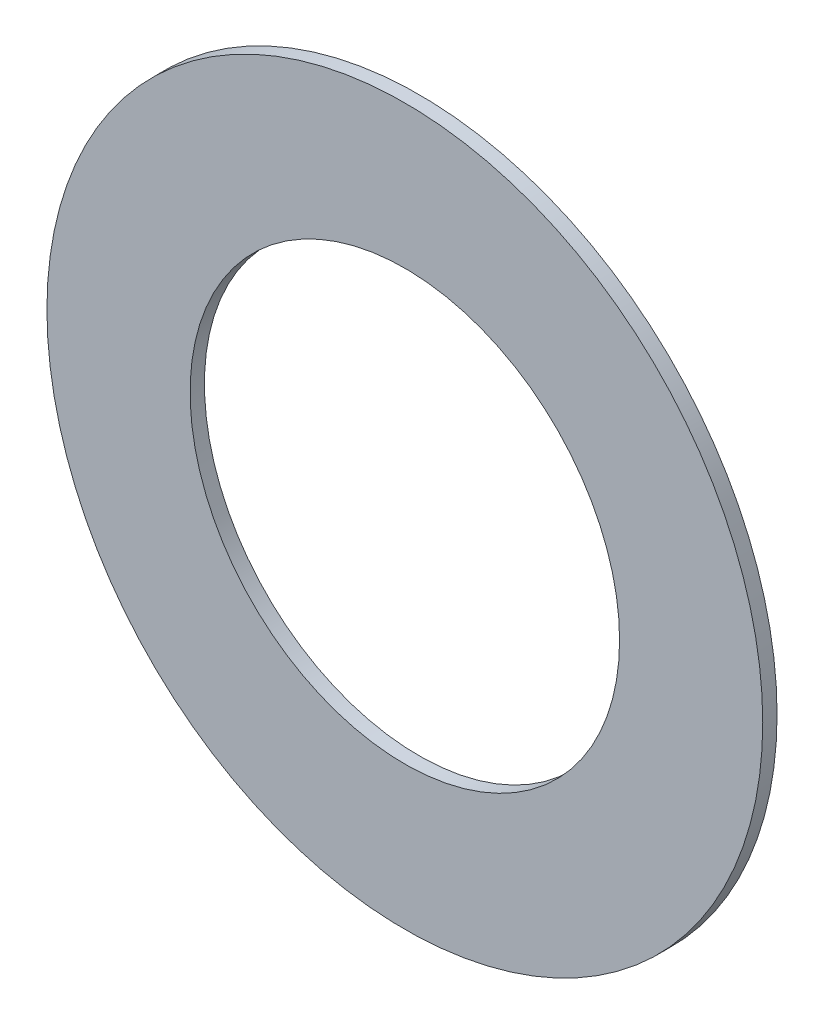
SolidWorks part; units mm, degrees
ref_plane "前视基准面" through (0, 0, 0) normal (0, 0, 1) x (1, 0, 0)
ref_plane "上视基准面" through (0, 0, 0) normal (0, 1, 0) x (1, 0, 0)
ref_plane "右视基准面" through (0, 0, 0) normal (1, 0, 0) x (0, 0, -1)
sketch "草图1" plane through (0, 0, 0) normal (0, 0, 1) x (1, 0, 0)
  circle A0 centre (0, 0) radius 1.5
  circle A1 centre (0, 0) radius 2.5
  dimension "D1" = 3
  dimension "D2" = 5
extrude "凸台-拉伸1" add sketch "草图1" along normal blind 0.1
